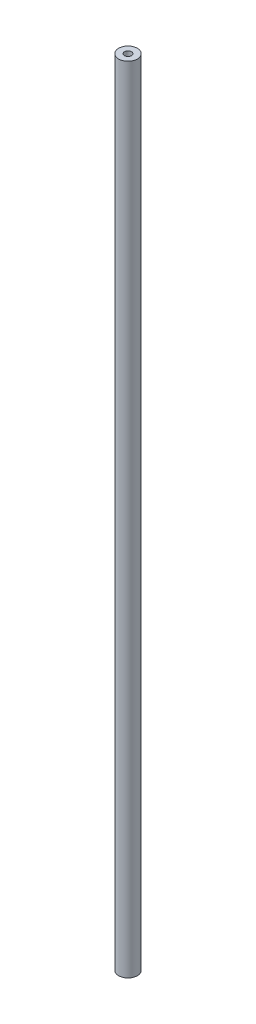
SolidWorks part; units mm, degrees
ref_plane "前视基准面" through (0, 0, 0) normal (0, 0, 1) x (1, 0, 0)
ref_plane "上视基准面" through (0, 0, 0) normal (0, 1, 0) x (1, 0, 0)
ref_plane "右视基准面" through (0, 0, 0) normal (1, 0, 0) x (0, 0, -1)
sketch "草图1" plane through (0, 0, 0) normal (0, 1, 0) x (1, 0, 0)
  circle A0 centre (-1.9321, 1.4107) radius 2
  circle A1 centre (-1.9321, 1.4107) radius 0.75
  dimension "D1" = 4
  dimension "D2" = 1.5
extrude "凸台-拉伸1" add sketch "草图1" along normal blind 170
